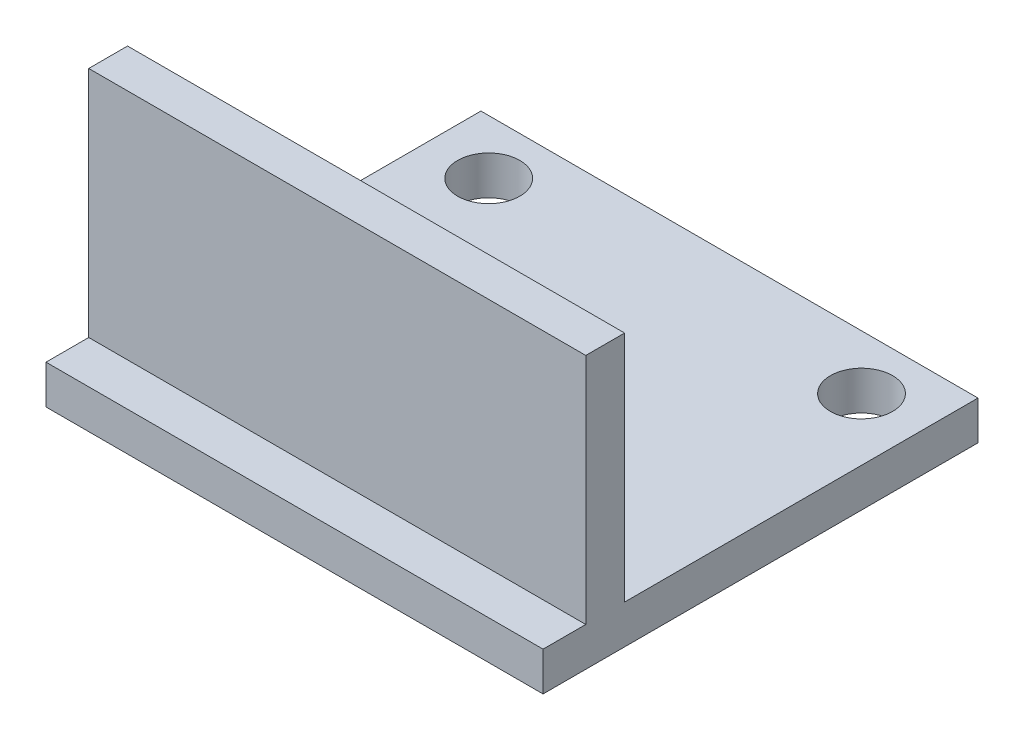
SolidWorks part; units mm, degrees
ref_plane "Front Plane" through (0, 0, 0) normal (0, 0, 1) x (1, 0, 0)
ref_plane "Top Plane" through (0, 0, 0) normal (0, 1, 0) x (1, 0, 0)
ref_plane "Right Plane" through (0, 0, 0) normal (1, 0, 0) x (0, 0, -1)
sketch "Sketch2" plane through (0, 0, 0) normal (0, 1, 0) x (1, 0, 0)
  line L0 (0, 8.89) -> (0, -8.89) construction
  line L1 (10.16, 8.89) -> (-10.16, 8.89)
  line L2 (10.16, 8.89) -> (10.16, -8.89)
  line L3 (10.16, -8.89) -> (-10.16, -8.89)
  line L4 (-10.16, 8.89) -> (-10.16, -8.89)
  line L5 (10.16, 8.89) -> (-10.16, -8.89) construction
  line L6 (10.16, -8.89) -> (-10.16, 8.89) construction
  circle A0 centre (-7.62, 6.6675) radius 1.27
  circle A1 centre (7.62, 6.6675) radius 1.27
  point P0 (0, 0)
  dimension "D3" = 2.54
  dimension "D1" = 17.78
  dimension "D2" = 20.32
  dimension "D4" = 7.62
extrude "Boss-Extrude1" add sketch "Sketch2" along normal blind 1.5875
sketch "Sketch3" plane through (0, 1.5875, 0) normal (0, 1, 0) x (1, 0, 0)
  line L0 (-10.16, -6.35) -> (10.16, -6.35) construction
  line L1 (-10.16, 8.89) -> (-10.16, -8.89) construction
  line L2 (-10.16, -8.89) -> (10.16, -8.89) construction
  line L3 (10.16, -8.89) -> (10.16, 8.89) construction
  line L5 (10.16, -5.5563) -> (-10.16, -5.5563)
  line L6 (10.16, -5.5563) -> (10.16, -7.1437)
  line L7 (10.16, -7.1437) -> (-10.16, -7.1437)
  line L8 (-10.16, -5.5563) -> (-10.16, -7.1437)
  line L9 (10.16, -5.5563) -> (-10.16, -7.1437) construction
  line L10 (10.16, -7.1437) -> (-10.16, -5.5563) construction
  point P9 (0, -6.35)
  dimension "D1" = 2.54
  dimension "D2" = 1.5875
extrude "Boss-Extrude2" add sketch "Sketch3" along normal blind 9.525
